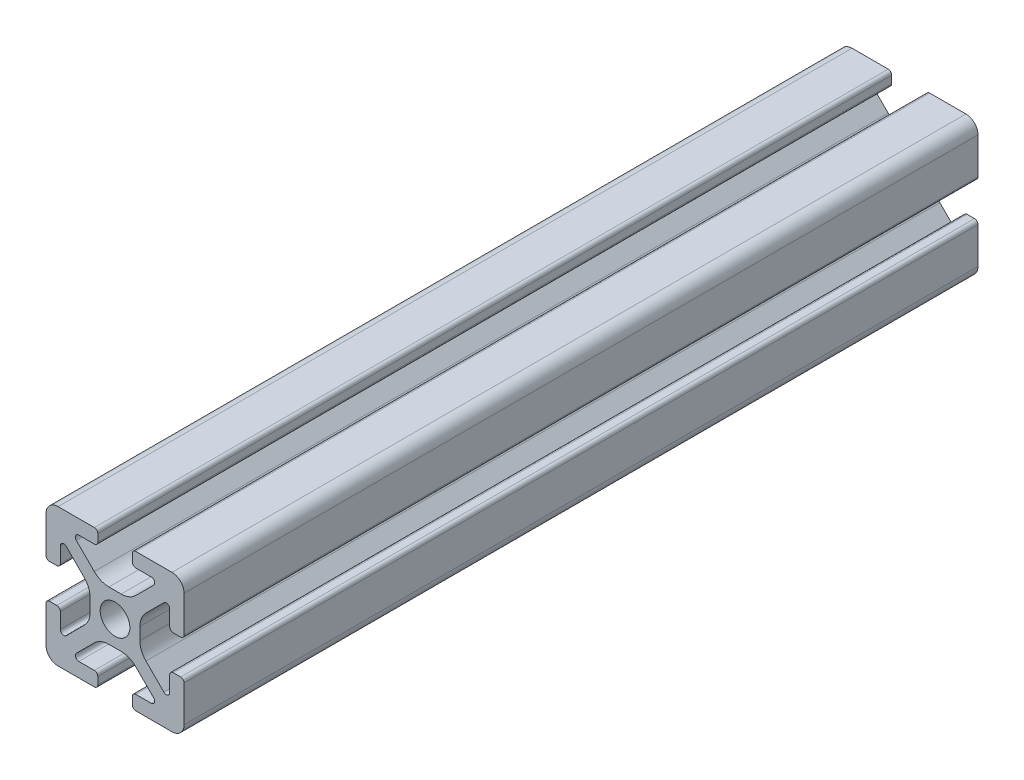
SolidWorks part; units mm, degrees
material "6063-T6"
ref_plane "Front Plane" through (0, 0, 0) normal (0, 0, 1) x (1, 0, 0)
ref_plane "Top Plane" through (0, 0, 0) normal (0, 1, 0) x (1, 0, 0)
ref_plane "Right Plane" through (0, 0, 0) normal (1, 0, 0) x (0, 0, -1)
sketch "Sketch2" plane through (0, 0, 0) normal (0, 0, 1) x (1, 0, 0)
  line L0 (0, 10) -> (0, -10) construction
  line L1 (-10, 0) -> (10, 0) construction
  line L2 (2.5, -10) -> (10, -10)
  line L3 (10, -10) -> (10, -2.5)
  line L4 (2.5, -10) -> (2.5, -7.9246)
  line L5 (2.5, -7.9246) -> (6.4571, -7.9246)
  line L6 (6.4571, -7.9246) -> (2.1325, -3.6)
  line L7 (0, 0) -> (10, -10) construction
  line L8 (10, -2.5) -> (7.9246, -2.5)
  line L9 (7.9246, -2.5) -> (7.9246, -6.4571)
  line L10 (7.9246, -6.4571) -> (3.6, -2.1325)
  line L11 (5.7623, -4.2948) -> (4.2948, -5.7623) construction
  circle A0 centre (0, 0) radius 2.15
  arc A1 (5.25, -7.9246) -> (5.6036, -7.0711) centre (5.25, -7.4246) ccw construction
  point P8 (0, -3.6)
  point P16 (5.0286, -5.0286)
  dimension "Center Hole Diameter" = 4.3
  dimension "D3" = 0.5
  dimension "Rail Height" = 20
  dimension "Rail Width" = 20
  dimension "T-Slot Width" = 5
  dimension "Slot Depth" = 6.4
  dimension "Slot Inner Width" = 11.5
sketch "Sketch3" plane through (0, 0, 0) normal (1, 0, 0) x (0, 0, -1)
  line L0 (-57.5, -10) -> (57.5, -10) construction
  line L1 (-32.1, 0) -> (32.1, 0) construction
  line L2 (0, 10) -> (0, -10) construction
  line L3 (0, 10) -> (0, -10) construction
  point P6 (-32.1, 0)
  point P8 (32.1, 0)
  dimension "Length" = 115
  dimension "D1" = 25.4
sketch "Sketch4" plane through (0, 0, 0) normal (0, 0, 1) x (1, 0, 0)
  line L0 (3, -10) -> (8.25, -10)
  line L1 (2.5, -10) -> (10, -10) construction
  line L2 (2.5, -10) -> (2.5, -7.9246) construction
  line L3 (2.5, -7.9246) -> (6.4571, -7.9246) construction
  line L4 (2.5, -8.4246) -> (2.5, -9.5)
  line L5 (3, -7.9246) -> (5.25, -7.9246)
  line L6 (0, -3.6) -> (0.8898, -3.6)
  line L7 (6.4571, -7.9246) -> (2.1325, -3.6) construction
  line L8 (3.0112, -4.4787) -> (5.6036, -7.0711)
  line L9 (10, -10) -> (10, -2.5) construction
  line L10 (7.9246, -6.4571) -> (3.6, -2.1325) construction
  line L11 (7.9246, -2.5) -> (7.9246, -6.4571) construction
  line L12 (7.9246, -5.25) -> (7.9246, -3)
  line L13 (10, -2.5) -> (7.9246, -2.5) construction
  line L14 (8.4246, -2.5) -> (9.5, -2.5)
  line L15 (10, -3) -> (10, -8.25)
  line L16 (7.0711, -5.6036) -> (4.4787, -3.0112)
  line L17 (3.6, 0) -> (3.6, -0.8898)
  line L18 (-10, 0) -> (10, 0) construction
  line L19 (0, -3.6) -> (0, -2.15)
  line L20 (0, 10) -> (0, -10) construction
  line L21 (3.6, 0) -> (2.15, 0)
  arc A0 (2.5, -9.5) -> (3, -10) centre (3, -9.5) ccw
  arc A1 (5.25, -7.9246) -> (5.6036, -7.0711) centre (5.25, -7.4246) ccw construction
  arc A2 (2.5, -8.4246) -> (3, -7.9246) centre (3, -8.4246) cw
  arc A3 (5.25, -7.9246) -> (5.6036, -7.0711) centre (5.25, -7.4246) ccw
  arc A4 (0.8898, -3.6) -> (3.0112, -4.4787) centre (0.8898, -6.6) cw
  arc A5 (8.25, -10) -> (10, -8.25) centre (8.25, -8.25) ccw
  arc A6 (7.0711, -5.6036) -> (7.9246, -5.25) centre (7.4246, -5.25) ccw
  arc A7 (7.9246, -3) -> (8.4246, -2.5) centre (8.4246, -3) cw
  arc A8 (9.5, -2.5) -> (10, -3) centre (9.5, -3) cw
  arc A9 (4.4787, -3.0112) -> (3.6, -0.8898) centre (6.6, -0.8898) cw
  circle A10 centre (0, 0) radius 2.15 construction
  arc A11 (0, -2.15) -> (2.15, 0) centre (0, 0) ccw
  dimension "D1" = 1.75
  dimension "D2" = 3
extrude "Boss-Extrude1" add sketch "Sketch4" along normal mid plane 115
mirror "Mirror1" about plane through (0, 0, 0) normal (1, 0, 0) of bodies 134
mirror "Mirror2" about plane through (0, 0, 0) normal (0, 1, 0) of bodies 135
sketch "Sketch5" plane through (-10, 0, 0) normal (-1, 0, 0) x (0, 0, 1)
  line L0 (57.5, -0.8898) -> (57.5, 0.8898) construction
  circle A0 centre (47.5, 0) radius 4
  dimension "D1" = 10
extrude "Cut-Extrude1" [suppressed] cut sketch "Sketch5" against normal blind 20
equation "\"D3@Sketch2\"=\"T-Slot Width@Sketch2\"*0.1"
equation "\"D1@Sketch4\"=\"D3@Sketch2\"*3.5"
equation "\"D2@Sketch4\"=\"D3@Sketch2\"*6"
equation "\"D1@Boss-Extrude1\"=\"Length@Sketch3\""
